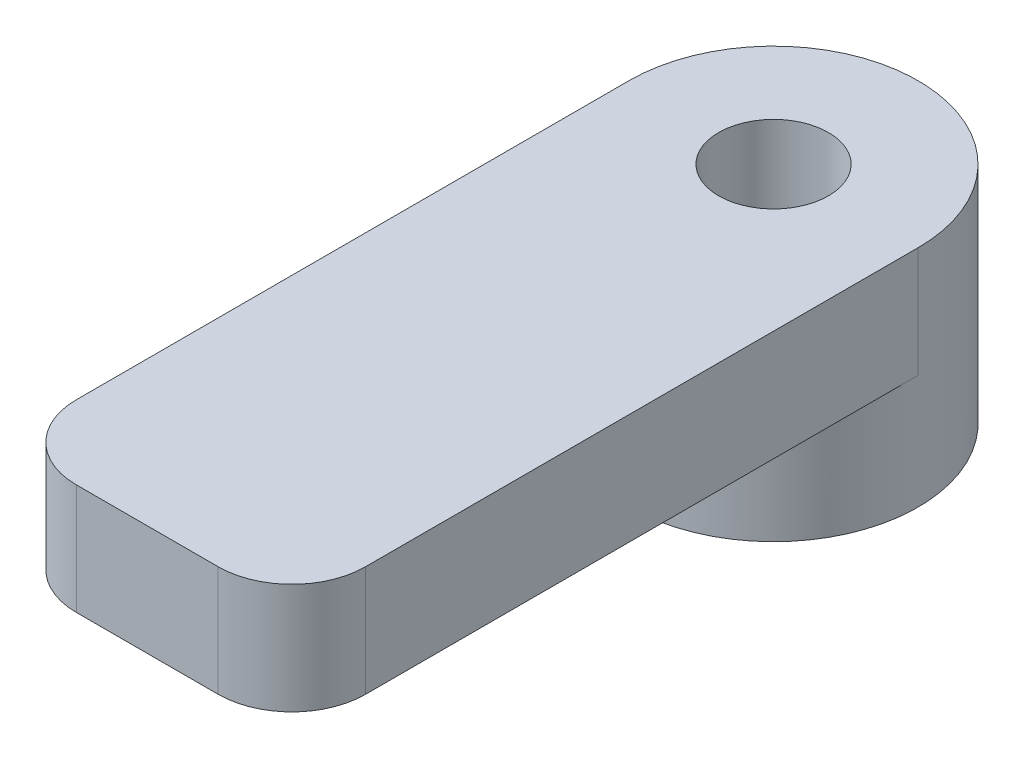
SolidWorks part; units mm, degrees
ref_plane "Front Plane" through (0, 0, 0) normal (0, 0, 1) x (1, 0, 0)
ref_plane "Top Plane" through (0, 0, 0) normal (0, 1, 0) x (1, 0, 0)
ref_plane "Right Plane" through (0, 0, 0) normal (1, 0, 0) x (0, 0, -1)
sketch "Sketch1" plane through (0, 0, 0) normal (0, 1, 0) x (1, 0, 0)
  circle A0 centre (0, 0) radius 3.925
  dimension "D1" = 7.85
extrude "Boss-Extrude1" add sketch "Sketch1" along normal blind 3.1
sketch "Sketch2" plane through (0, 3.1, 0) normal (0, 1, 0) x (1, 0, 0)
  circle A0 centre (0, 0) radius 1.49
  dimension "D1" = 2.98
extrude "Cut-Extrude1" cut sketch "Sketch2" against normal blind 3.1
sketch "Sketch3" plane through (0, 3.1, 0) normal (0, 1, 0) x (1, 0, 0)
  line L0 (-3.925, 0) -> (-3.925, -15)
  line L1 (-1.925, -17) -> (1.925, -17)
  line L2 (3.925, -15) -> (3.925, 0)
  circle A0 centre (0, 0) radius 3.925 construction
  arc A1 (1.925, -17) -> (3.925, -15) centre (1.925, -15) ccw
  arc A2 (-3.925, -15) -> (-1.925, -17) centre (-1.925, -15) ccw
  arc A3 (-3.925, 0) -> (3.925, 0) centre (0, 0) cw
  circle A4 centre (0, 0) radius 1.49
  dimension "D1" = 2
  dimension "D2" = 15
extrude "Boss-Extrude2" add sketch "Sketch3" along normal blind 3
